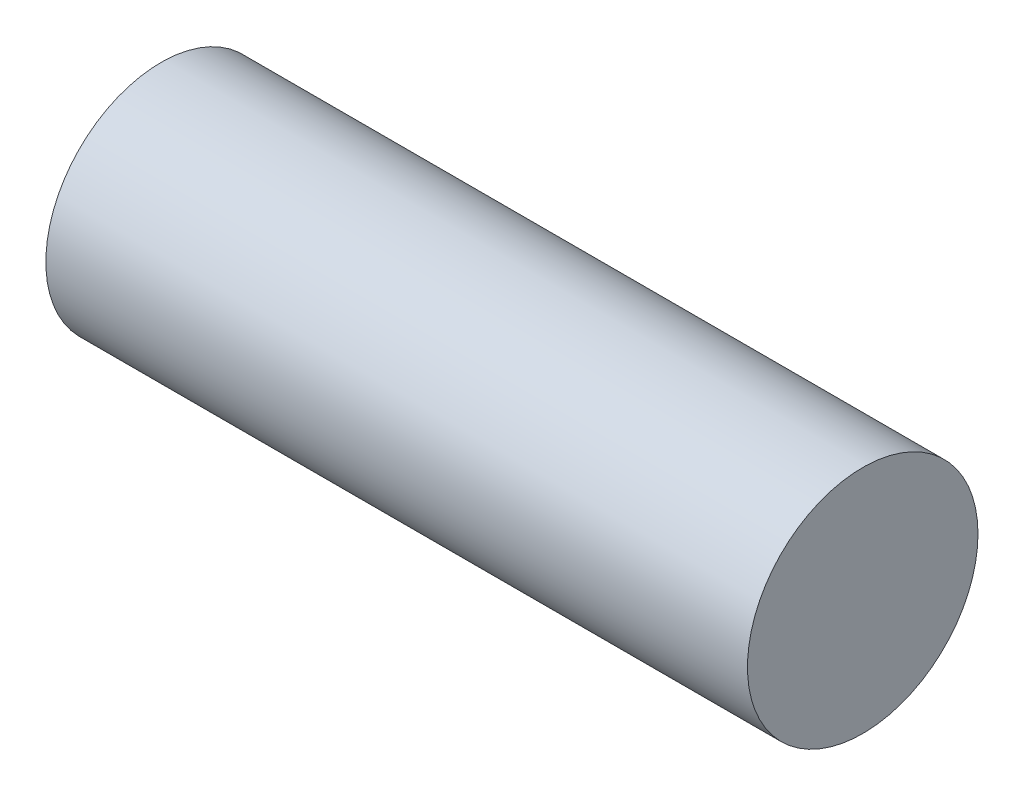
SolidWorks part; units mm, degrees
material "ABS"
ref_plane "Front Plane" through (0, 0, 0) normal (0, 0, 1) x (1, 0, 0)
ref_plane "Top Plane" through (0, 0, 0) normal (0, 1, 0) x (1, 0, 0)
ref_plane "Right Plane" through (0, 0, 0) normal (1, 0, 0) x (0, 0, -1)
sketch "Sketch1" plane through (0, 0, 0) normal (1, 0, 0) x (0, 0, -1)
  circle A0 centre (0, 0) radius 2.3
  dimension "D1" = 4.6
extrude "peg" add sketch "Sketch1" along normal mid plane 14
equation "\"D1@Sketch1\"=2*2.3mm"
